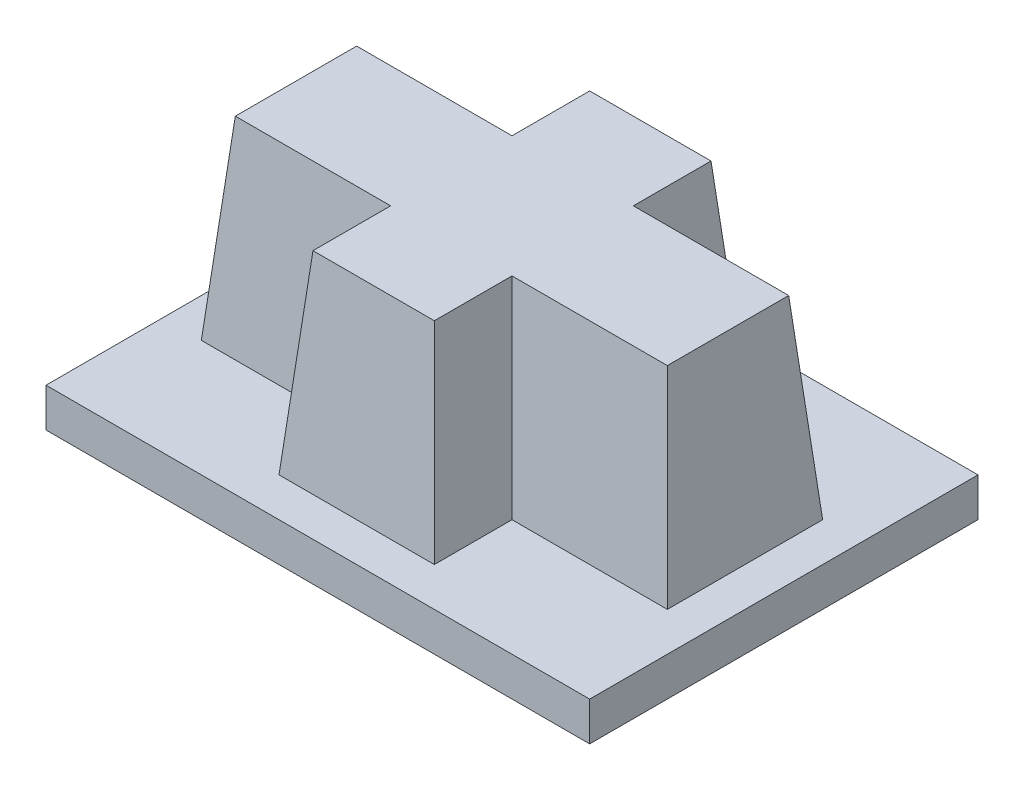
SolidWorks part; units mm, degrees
ref_plane "정면" through (0, 0, 0) normal (0, 0, 1) x (1, 0, 0)
ref_plane "윗면" through (0, 0, 0) normal (0, 1, 0) x (1, 0, 0)
ref_plane "우측면" through (0, 0, 0) normal (1, 0, 0) x (0, 0, -1)
sketch "스케치1" plane through (0, 0, 0) normal (0, 1, 0) x (1, 0, 0)
  line L1 (-70, 50) -> (70, 50)
  line L2 (-70, 50) -> (-70, -50)
  line L3 (-70, -50) -> (70, -50)
  line L4 (70, 50) -> (70, -50)
  line L5 (-70, 50) -> (70, -50) construction
  line L6 (-70, -50) -> (70, 50) construction
  point P0 (0, 0)
  dimension "D1" = 140
  dimension "D2" = 100
extrude "보스-돌출1" add sketch "스케치1" along normal blind 10
sketch "스케치2" plane through (0, 10, 0) normal (0, 1, 0) x (1, 0, 0)
  line L0 (20, 20) -> (60, 20)
  line L1 (-60, 20) -> (-20, 20)
  line L2 (-60, 20) -> (-60, -20)
  line L3 (-60, -20) -> (-20, -20)
  line L4 (60, 20) -> (60, -20)
  line L7 (-20, 40) -> (20, 40)
  line L8 (-20, 40) -> (-20, 20)
  line L9 (-20, -40) -> (20, -40)
  line L10 (20, 40) -> (20, 20)
  line L14 (-20, -20) -> (-20, -40)
  line L16 (20, -20) -> (60, -20)
  line L17 (20, -20) -> (20, -40)
  point P0 (0, 0)
  point P6 (0, 0)
  dimension "D1" = 40
  dimension "D2" = 40
  dimension "D3" = 80
  dimension "D4" = 120
extrude "보스-돌출2" add sketch "스케치2" along normal blind 50 draft 5
